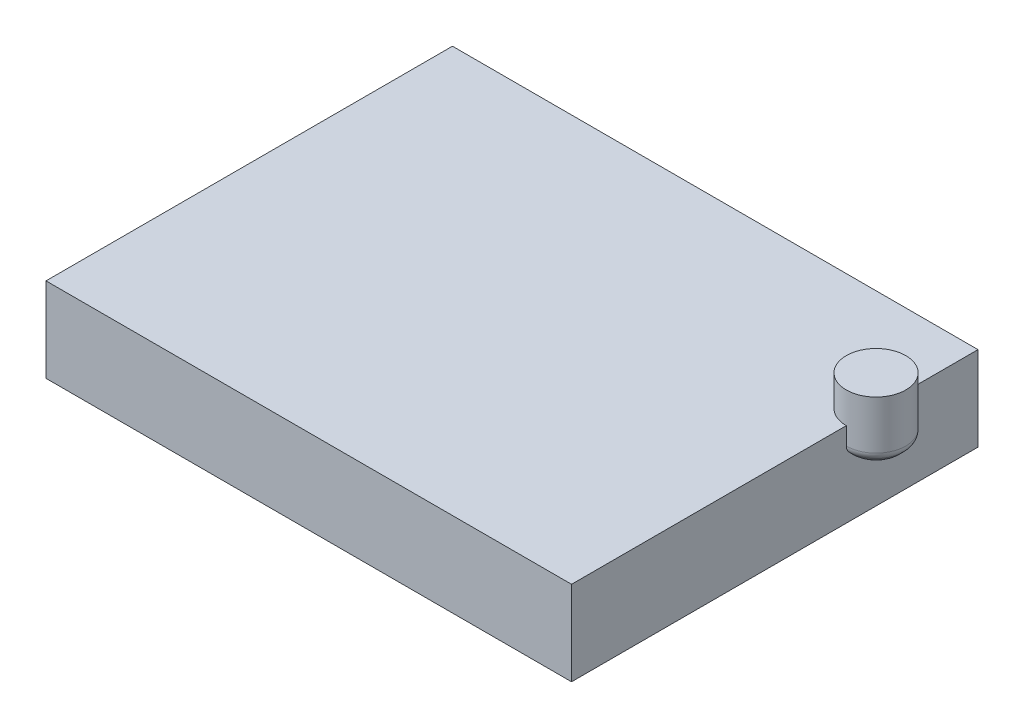
SolidWorks part; units mm, degrees
ref_plane "Front Plane" through (0, 0, 0) normal (0, 0, 1) x (1, 0, 0)
ref_plane "Top Plane" through (0, 0, 0) normal (0, 1, 0) x (1, 0, 0)
ref_plane "Right Plane" through (0, 0, 0) normal (1, 0, 0) x (0, 0, -1)
sketch "Sketch1" plane through (0, 0, 0) normal (1, 0, 0) x (0, 0, -1)
  line L1 (-68.7535, 25.4) -> (68.7535, 25.4)
  line L2 (-68.7535, 25.4) -> (-68.7535, -3.175)
  line L3 (-68.7535, -3.175) -> (68.7535, -3.175)
  line L4 (68.7535, 25.4) -> (68.7535, -3.175)
  point P0 (0, 0)
  dimension "D1" = 3.175
  dimension "D2" = 25.4
extrude "Extrude1" add sketch "Sketch1" against normal blind 177.8
sketch "Sketch2" plane through (0, 0, 0) normal (1, 0, 0) x (0, 0, -1)
  line L0 (34.2633, 35.8608) -> (34.2633, 14.9392)
  line L1 (42.087, 15.8691) -> (43.4021, 17.1842)
  line L3 (34.2633, 14.9392) -> (34.2061, 15.0712)
  line L7 (34.2633, 35.8608) -> (44.3321, 35.8608)
  line L9 (34.2633, 14.9392) -> (39.8419, 14.9392)
  line L10 (44.3321, 35.8608) -> (44.3321, 19.4293)
  arc A2 (42.087, 15.8691) -> (39.8419, 14.9392) centre (39.8419, 18.1142) cw
  arc A3 (43.4021, 17.1842) -> (44.3321, 19.4293) centre (41.1571, 19.4293) ccw
  point P0 (34.2633, 25.4)
  point P1 (34.2633, 25.4)
  point P2 (44.3321, 22.6703)
  point P4 (24.1945, 22.6703)
  point P5 (34.2633, 25.4)
  point P11 (24.1945, 18.1142)
  point P13 (24.1945, 25.8453)
  point P17 (41.1571, 14.9392)
  point P18 (41.1571, 22.6703)
  point P21 (34.2633, 25.4)
  point P22 (44.3321, 14.9392)
  point P25 (24.1945, 14.9392)
  dimension "D5" = 3.175
  dimension "D6" = 45
  dimension "D3" = 3.175
ref_plane "Plane1" through (0, 25.4, 0) normal (0, 1, 0) x (-1, 0, 0)
sketch "Sketch3" plane through (0, 25.4, 0) normal (0, 1, 0) x (-1, 0, 0)
  line L0 (0, -34.2633) -> (67.4966, -34.2633)
  line L2 (0, -68.7535) -> (0, 68.7535) construction
  line L3 (75.8052, -35.6606) -> (98.3925, -43.4793)
  line L4 (0, 0) -> (103.7748, 0) construction
  line L5 (75.8052, 35.6606) -> (98.3925, 43.4793)
  line L6 (0, 34.2633) -> (67.4966, 34.2633)
  arc A0 (112.2909, -44.2539) -> (112.2909, 44.2539) centre (102.307, 0) ccw
  arc A1 (98.3925, 43.4793) -> (112.2909, 44.2539) centre (106.7011, 19.4767) cw
  arc A2 (98.3925, -43.4793) -> (112.2909, -44.2539) centre (106.7011, -19.4767) ccw
  arc A3 (75.8052, 35.6606) -> (67.4966, 34.2633) centre (67.4966, 59.6633) cw
  arc A4 (67.4966, -34.2633) -> (75.8052, -35.6606) centre (67.4966, -59.6633) cw
  point P15 (103.7748, 45.3424)
  point P18 (103.7748, -45.3424)
  point P21 (71.7684, 34.2633)
  point P24 (71.7684, -34.2633)
  dimension "D1" = 25.4
revolve "Revolve1" add sketch "Sketch2" angle 360 about L0
